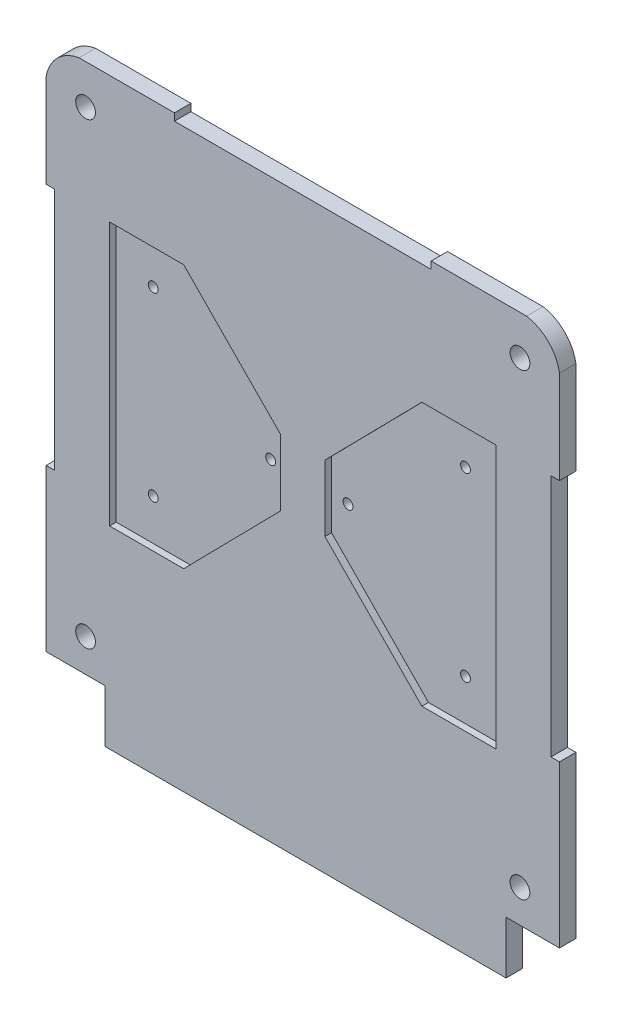
SolidWorks part; units mm, degrees
ref_plane "Front Plane" through (0, 0, 0) normal (0, 0, 1) x (1, 0, 0)
ref_plane "Top Plane" through (0, 0, 0) normal (0, 1, 0) x (1, 0, 0)
ref_plane "Right Plane" through (0, 0, 0) normal (1, 0, 0) x (0, 0, -1)
sketch "Sketch1" plane through (0, 0, 0) normal (0, 0, 1) x (1, 0, 0)
  line L0 (-75.42, 42.35) -> (-75.42, -31.65)
  line L1 (-75.42, -31.65) -> (-78, -31.65)
  line L2 (-78, -31.65) -> (-78, -80.65)
  line L3 (-78, -80.65) -> (78, -80.65)
  line L4 (78, -80.65) -> (78, -31.65)
  line L5 (78, -31.65) -> (75.4199, -31.65)
  line L6 (75.4199, -31.65) -> (75.4199, 42.35)
  line L7 (75.4199, 42.35) -> (78, 42.35)
  line L8 (78, 42.35) -> (78, 70.65)
  line L9 (68, 80.65) -> (39, 80.65)
  line L10 (39, 80.65) -> (39, 78.45)
  line L11 (39, 78.45) -> (-39, 78.45)
  line L12 (-39, 78.45) -> (-39, 80.65)
  line L13 (-39, 80.65) -> (-68, 80.65)
  line L14 (-78, 70.65) -> (-78, 42.35)
  line L15 (-78, 42.35) -> (-75.42, 42.35)
  arc A0 (78, 70.65) -> (68, 80.65) centre (65.9999, 68.6499) ccw
  arc A1 (-68, 80.65) -> (-78, 70.65) centre (-66.0001, 68.6501) ccw
extrude "Boss-Extrude1" add sketch "Sketch1" along normal blind 5
ref_plane "Plane1" through (0, 0, 0) normal (-0.7071, 0.7071, 0) x (0.7071, 0.7071, 0)
sketch "Sketch2" plane through (0, 0, 5) normal (0, 0, 1) x (1, 0, 0)
  line L20 (-6.7394, -7.9751) -> (-6.7394, 12.1391)
  line L21 (-6.7394, -7.9751) -> (-36.1915, -37.918)
  line L22 (-36.1915, -37.918) -> (-58.6915, -37.918)
  line L23 (-58.6915, -37.918) -> (-58.6915, 2.082)
  line L24 (-58.6915, 42.082) -> (-58.6915, 2.082)
  line L25 (-36.1915, 42.082) -> (-58.6915, 42.082)
  line L26 (-6.7394, 12.1391) -> (-36.1915, 42.082)
  line L27 (0, -2.75) -> (0, 2.75) construction
  line L28 (6.7394, 12.1391) -> (36.1915, 42.082)
  line L29 (36.1915, 42.082) -> (58.6915, 42.082)
  line L30 (58.6915, 42.082) -> (58.6915, 2.082)
  line L31 (58.6915, -37.918) -> (58.6915, 2.082)
  line L32 (36.1915, -37.918) -> (58.6915, -37.918)
  line L33 (6.7394, -7.9751) -> (36.1915, -37.918)
  line L34 (6.7394, -7.9751) -> (6.7394, 12.1391)
extrude "Cut-Extrude1" cut sketch "Sketch2" against normal blind 2
sketch "Sketch3" plane through (0, 0, 5) normal (0, 0, 1) x (1, 0, 0)
  line L0 (-74.6023, 77.2523) -> (-66.0001, 68.6501) construction
  line L1 (74.6023, 77.2523) -> (65.9999, 68.6499) construction
  line L2 (-66.0001, -80.65) -> (-66.0001, -70.65) construction
  line L3 (-78, -80.65) -> (78, -80.65) construction
  line L4 (65.9999, -80.65) -> (65.9999, -70.65) construction
  arc A0 (-68, 80.65) -> (-78, 70.65) centre (-66.0001, 68.6501) ccw construction
  circle A1 centre (-66.0001, 68.6501) radius 3
  arc A2 (78, 70.65) -> (68, 80.65) centre (65.9999, 68.6499) ccw construction
  circle A3 centre (65.9999, 68.6499) radius 3
  circle A4 centre (-66.0001, -70.65) radius 3
  circle A5 centre (65.9999, -70.65) radius 3
extrude "Cut-Extrude2" cut sketch "Sketch3" against normal blind 42
sketch "Sketch6" plane through (0, 0, 0) normal (0, 0, -1) x (-1, 0, 0)
  line L0 (-59.9951, -61.6656) -> (61.5049, -61.6656) construction
  line L1 (-63.9951, -59.6656) -> (-59.9951, -59.6656)
  line L2 (-63.9951, -59.6656) -> (-63.9951, -63.6656)
  line L3 (-63.9951, -63.6656) -> (-59.9951, -63.6656)
  line L4 (-59.9951, -59.6656) -> (-59.9951, -63.6656)
  line L5 (-63.9951, -59.6656) -> (-59.9951, -63.6656) construction
  line L6 (-63.9951, -63.6656) -> (-59.9951, -59.6656) construction
  line L7 (61.5049, -59.6656) -> (65.5049, -59.6656)
  line L8 (61.5049, -59.6656) -> (61.5049, -63.6656)
  line L9 (61.5049, -63.6656) -> (65.5049, -63.6656)
  line L10 (65.5049, -59.6656) -> (65.5049, -63.6656)
  line L11 (61.5049, -59.6656) -> (65.5049, -63.6656) construction
  line L12 (61.5049, -63.6656) -> (65.5049, -59.6656) construction
  point P4 (-61.9951, -61.6656)
  point P9 (63.5049, -61.6656)
extrude "Cut-Extrude4" cut sketch "Sketch6" against normal blind 3
sketch "Sketch7" plane through (0, 0, 0) normal (0, 0, -1) x (-1, 0, 0)
  line L0 (-63.9951, -59.6656) -> (-63.9951, 47.6605)
  line L1 (65.5049, -59.6656) -> (65.5049, 47.6605)
  line L2 (65.5049, 47.6605) -> (-63.9951, 47.6605)
  line L3 (-59.9951, -59.6656) -> (-59.9951, 44.4761)
  line L4 (61.5049, -59.6656) -> (61.5049, 44.4761)
  line L5 (61.5049, 44.4761) -> (-59.9951, 44.4761)
  line L6 (-63.9951, -59.6656) -> (-59.9951, -59.6656)
  line L7 (61.5049, -59.6656) -> (65.5049, -59.6656)
extrude "Cut-Extrude5" cut sketch "Sketch7" against normal blind 3
sketch "Sketch8" plane through (0, 0, 0) normal (0, 0, -1) x (-1, 0, 0)
  line L0 (-61.77, -80.65) -> (60.13, -80.65)
  line L1 (78, -80.65) -> (-78, -80.65) construction
  line L3 (-61.77, -80.65) -> (60.13, -80.65)
  line L4 (-61.77, -80.65) -> (-61.77, -96.65)
  line L5 (-61.77, -96.65) -> (60.13, -96.65)
  line L6 (60.13, -80.65) -> (60.13, -96.65)
  line L7 (-61.77, -80.65) -> (60.13, -96.65) construction
  line L8 (-61.77, -96.65) -> (60.13, -80.65) construction
  point P5 (-0.82, -80.65)
  point P7 (-0.82, -88.65)
  line M28 (-78, -80.65) -> (78, -80.65)
  dimension "D1" = 16
extrude "Boss-Extrude2" add sketch "Sketch8" against normal blind 5 contours L6 L4 L5 M28
sketch "Sketch10" plane through (0, 0, 3) normal (0, 0, 1) x (1, 0, 0)
  line L0 (-47.4415, 42.082) -> (-47.4415, 29.582) construction
  line L1 (-36.1915, 42.082) -> (-58.6915, 42.082) construction
  line L2 (-47.4415, -37.918) -> (-47.4415, -25.418) construction
  line L3 (-58.6915, -37.918) -> (-36.1915, -37.918) construction
  line L4 (-6.7394, 2.082) -> (-11.7594, 2.082) construction
  line L5 (-6.7394, -7.9751) -> (-6.7394, 12.1391) construction
  line L6 (0, -2.75) -> (0, 2.75) construction
  line L7 (47.4415, -37.918) -> (47.4415, -25.418) construction
  line L8 (47.4415, 42.082) -> (47.4415, 29.582) construction
  line L9 (6.7394, 2.082) -> (11.7594, 2.082) construction
  circle A0 centre (-47.4415, 29.582) radius 1.5
  circle A1 centre (-47.4415, -25.418) radius 1.5
  circle A2 centre (-11.7594, 2.082) radius 1.5
  circle A3 centre (11.7594, 2.082) radius 1.5
  circle A4 centre (47.4415, -25.418) radius 1.5
  circle A5 centre (47.4415, 29.582) radius 1.5
extrude "Cut-Extrude6" cut sketch "Sketch10" against normal blind 10
